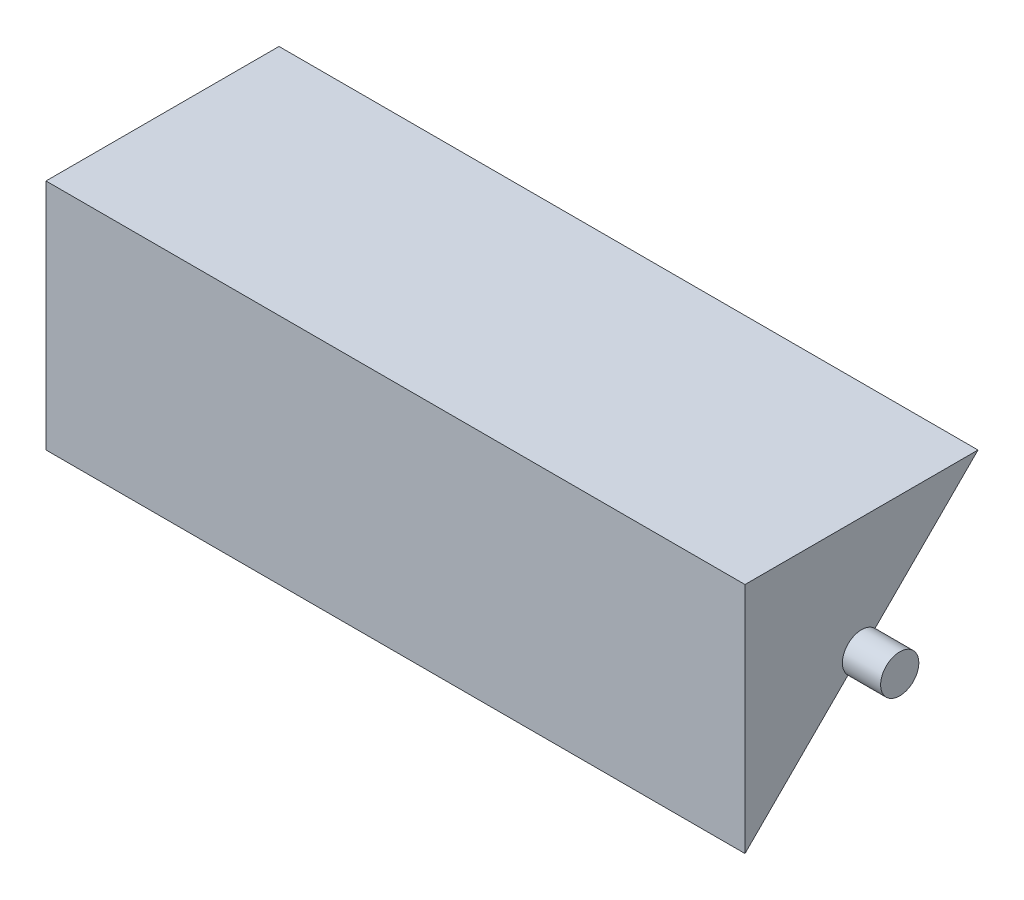
SolidWorks part; units mm, degrees
ref_plane "Front Plane" through (0, 0, 0) normal (0, 0, 1) x (1, 0, 0)
ref_plane "Top Plane" through (0, 0, 0) normal (0, 1, 0) x (1, 0, 0)
ref_plane "Right Plane" through (0, 0, 0) normal (1, 0, 0) x (0, 0, -1)
sketch "Sketch1" plane through (0, 0, 0) normal (0, 0, 1) x (1, 0, 0)
  line L1 (-457.2, -152.4) -> (457.2, -152.4)
  line L2 (-457.2, -152.4) -> (-457.2, 152.4)
  line L3 (-457.2, 152.4) -> (457.2, 152.4)
  line L4 (457.2, -152.4) -> (457.2, 152.4)
  line L5 (-457.2, -152.4) -> (457.2, 152.4) construction
  line L6 (-457.2, 152.4) -> (457.2, -152.4) construction
  point P0 (0, 0)
  dimension "D1" = 304.8
  dimension "D2" = 914.4
extrude "Boss-Extrude1" add sketch "Sketch1" along normal blind 304.8
sketch "Sketch2" plane through (457.2, 0, 0) normal (1, 0, 0) x (0, 0, -1)
  line L0 (-304.8, -152.4) -> (0, 152.4)
  line L1 (0, 152.4) -> (0, -152.4)
  line L2 (0, -152.4) -> (-304.8, -152.4)
extrude "Cut-Extrude1" cut sketch "Sketch2" against normal up to surface (914.4 mm away) up to face at (-457.2, 0, 152.4)
sketch "Sketch3" plane through (457.2, 0, 0) normal (1, 0, 0) x (0, 0, -1)
  line L0 (0, 152.4) -> (-304.8, -152.4) construction
  circle A0 centre (-152.4, 0) radius 25
  dimension "D1" = 50
extrude "Boss-Extrude2" add sketch "Sketch3" along normal blind 50 and the other way blind 976
